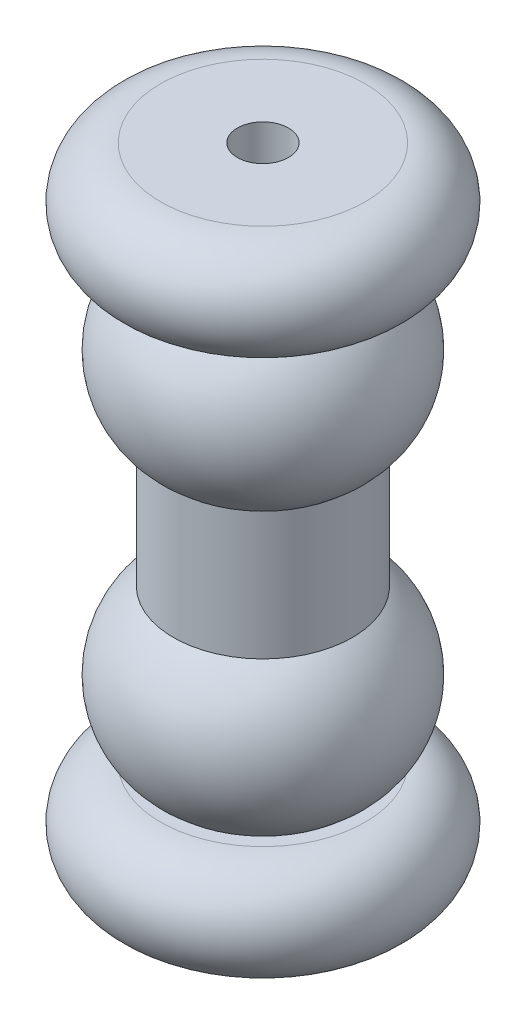
SolidWorks part; units mm, degrees
material "Silicon"
ref_plane "Front" through (0, 0, 0) normal (0, 0, 1) x (1, 0, 0)
ref_plane "Top" through (0, 0, 0) normal (0, 1, 0) x (1, 0, 0)
ref_plane "Right" through (0, 0, 0) normal (1, 0, 0) x (0, 0, -1)
sketch "Sketch1" plane through (0, 0, 0) normal (0, 0, 1) x (1, 0, 0)
  line L0 (0, 0) -> (0, 25) construction
  line L1 (0, 25) -> (4, 25)
  line L2 (4, 21) -> (3.5, 21)
  line L3 (3.5, 15) -> (3.5, 10)
  line L4 (0, 12.5) -> (3.5, 12.5) construction
  line L5 (4, 4) -> (3.5, 4)
  line L6 (0, 0) -> (4, 0)
  line L7 (1, 25) -> (1, 0)
  arc A0 (4, 25) -> (4, 21) centre (4, 23) cw
  arc A1 (3.5, 21) -> (3.5, 15) centre (1.25, 18) cw
  arc A2 (3.5, 4) -> (3.5, 10) centre (1.25, 7) ccw
  arc A3 (4, 0) -> (4, 4) centre (4, 2) ccw
  point P12 (6, 23)
  point P13 (5, 18)
  dimension "D2" = 6
  dimension "D1" = 25
  dimension "D3" = 5
  dimension "D4" = 3.5
  dimension "D5" = 4
  dimension "D6" = 5
  dimension "D7" = 2
revolve "Revolve1" add sketch "Sketch1" angle 360 about L0
